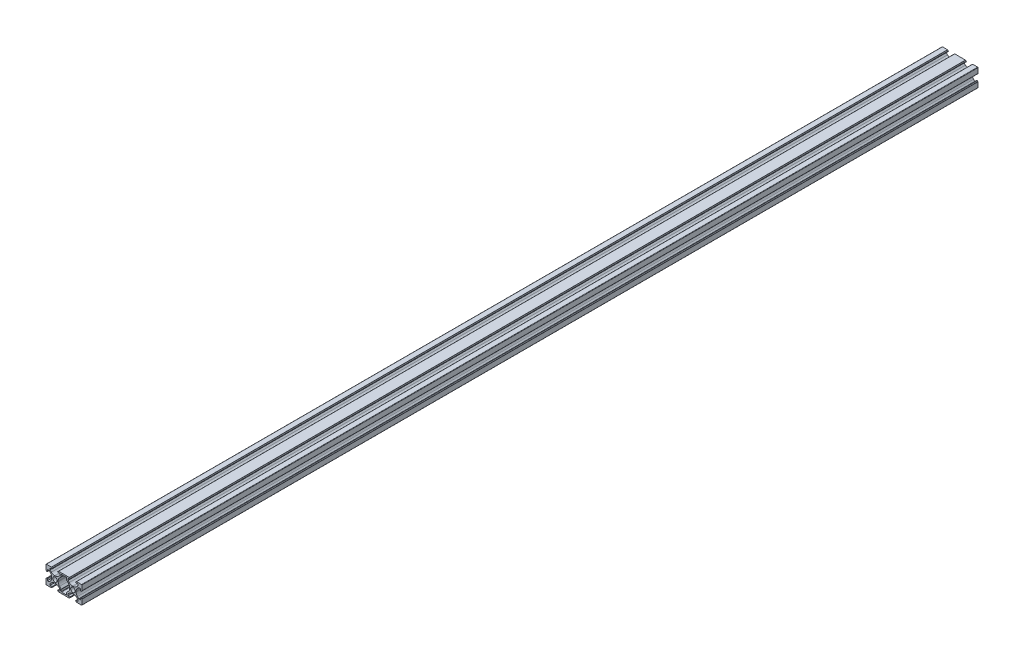
SolidWorks part; units mm, degrees
material "6063-O"
ref_plane "Plano frontal" through (0, 0, 0) normal (0, 0, 1) x (1, 0, 0)
ref_plane "Plano superior" through (0, 0, 0) normal (0, 1, 0) x (1, 0, 0)
ref_plane "Plano direito" through (0, 0, 0) normal (1, 0, 0) x (0, 0, -1)
sketch "Esboço1" plane through (0, 0, 0) normal (0, 0, 1) x (1, 0, 0)
  line L0 (-9.0343, 3.1) -> (-8.9, 3.1)
  line L3 (-10, 10) -> (-4.0657, 10)
  line L5 (-10, -10) -> (10, 10) construction
  line L6 (-10, 10) -> (10, -10) construction
  line L7 (-8.5, 3.5) -> (-8.5, 5.5)
  line L8 (-10, 0) -> (10, 0) construction
  line L9 (0, 10) -> (0, -10) construction
  line L12 (-8.5, 5.5) -> (-6.5607, 5.5)
  line L15 (-6.5607, 5.5) -> (-5.0645, 4.0038)
  line L16 (-3.6, 0.4683) -> (-3.6, 0)
  line L17 (-0.4683, 3.6) -> (0, 3.6)
  line L18 (-5.5, 6.5607) -> (-4.0038, 5.0645)
  line L21 (-5.5, 8.5) -> (-5.5, 6.5607)
  line L24 (-3.5, 8.5) -> (-5.5, 8.5)
  line L25 (-3.1, 9.0343) -> (-3.1, 8.9)
  line L44 (-10, 4.0657) -> (-10, 10)
  line L45 (-9.8828, 3.7828) -> (-9.3172, 3.2172)
  line L46 (-3.7828, 9.8828) -> (-3.2172, 9.3172)
  line L47 (-3.6, 0) -> (-2.5, 0)
  line L48 (0, 3.6) -> (0, 2.5)
  arc A0 (-3.5, 8.5) -> (-3.1, 8.9) centre (-3.5, 8.9) ccw
  arc A1 (-3.7828, 9.8828) -> (-4.0657, 10) centre (-4.0657, 9.6) ccw
  arc A2 (-10, 4.0657) -> (-9.8828, 3.7828) centre (-9.6, 4.0657) ccw
  arc A3 (-8.5, 3.5) -> (-8.9, 3.1) centre (-8.9, 3.5) cw
  arc A4 (-3.2172, 9.3172) -> (-3.1, 9.0343) centre (-3.5, 9.0343) cw
  arc A5 (-9.3172, 3.2172) -> (-9.0343, 3.1) centre (-9.0343, 3.5) ccw
  arc A6 (-3.6, 0.4683) -> (-5.0645, 4.0038) centre (-8.6, 0.4683) ccw
  arc A7 (-4.0038, 5.0645) -> (-0.4683, 3.6) centre (-0.4683, 8.6) ccw
  circle A8 centre (0, 0) radius 2.5
  point P6 (-10, 3.1)
  point P28 (-3.1, 8.5)
  point P31 (-3.1, 10)
  point P33 (-3.9, 10)
  point P36 (-10, 3.9)
  point P39 (-8.5, 3.1)
  point P42 (-3.1, 9.2)
  point P45 (-9.2, 3.1)
  point P48 (-3.6, 2.5393)
  point P51 (-2.5393, 3.6)
  dimension "D5" = 10
  dimension "D9" = 0.4
  dimension "D10" = 0.4
  dimension "D11" = 5
  dimension "D12" = 5
  dimension "D13" = 5
  dimension "D1" = 6.9
  dimension "D2" = 1.5
  dimension "D3" = 3.6
  dimension "D4" = 1.5
  dimension "D6" = 2.4
  dimension "D7" = 3.6
  dimension "D8" = 45
extrude "Ressalto-extrusão1" add sketch "Esboço1" along normal blind 1000
sketch "Esboço3" plane through (0, 0, 0) normal (1, 0, 0) x (0, 0, -1)
  line L0 (0, 0) -> (-1000, 0) construction
  dimension "D1" = 1000
pattern_circular "PadrãoCircular1" count 4 every 90 about axis through (0, 0, 0) along (0, 0, 1) of "Ressalto-extrusão1"
pattern_linear "Padrão linear1" count 2 spacing 20 along (1, 0, 0) of "Ressalto-extrusão1", "PadrãoCircular1"
sketch "Esboço4" plane through (0, 0, 0) normal (0, 0, -1) x (-1, 0, 0)
  line L0 (-13.4393, 5.5) -> (-13, 5.9393)
  line L1 (-13, 8.5) -> (-13, 5.9393)
  line L2 (-10, 10) -> (-10, -10) construction
  line L3 (-4.0657, 10) -> (-15.9343, 10) construction
  line L4 (-15.9343, -10) -> (-4.0657, -10) construction
  line L5 (-11.5, 5.5) -> (-13.4393, 5.5) construction
  line L6 (-14.5, 8.5) -> (-14.5, 6.5607) construction
  line L7 (-7, 8.5) -> (-7, 5.9393)
  line L8 (-6.5607, 5.5) -> (-7, 5.9393)
  line L9 (-13, 8.5) -> (-7, 8.5)
  line L10 (-20, 0) -> (0, 0) construction
  line L11 (-13, -8.5) -> (-7, -8.5)
  line L12 (-6.5607, -5.5) -> (-7, -5.9393)
  line L13 (-7, -8.5) -> (-7, -5.9393)
  line L14 (-13, -8.5) -> (-13, -5.9393)
  line L15 (-13.4393, -5.5) -> (-13, -5.9393)
  line L16 (-13.4393, 5.5) -> (-13.4393, -5.5)
  line L17 (-6.5607, -5.5) -> (-6.5607, 5.5)
  dimension "D1" = 45
  dimension "D2" = 1.5
  dimension "D3" = 1.5
extrude "Corte-extrusão1" cut sketch "Esboço4" against normal through all
fillet "Filete1" radius 0.4 8 edges at (13, -5.9393, 500) (13, -8.5, 500) (7, -8.5, 500) (7, -5.9393, 500) (7, 8.5, 500) (7, 5.9393, 500) (13, 8.5, 500) (13, 5.9393, 500)
fillet "Filete2" radius 0.4 4 edges at (30, -10, 500) (30, 10, 500) (-10, 10, 500) (-10, -10, 500)
